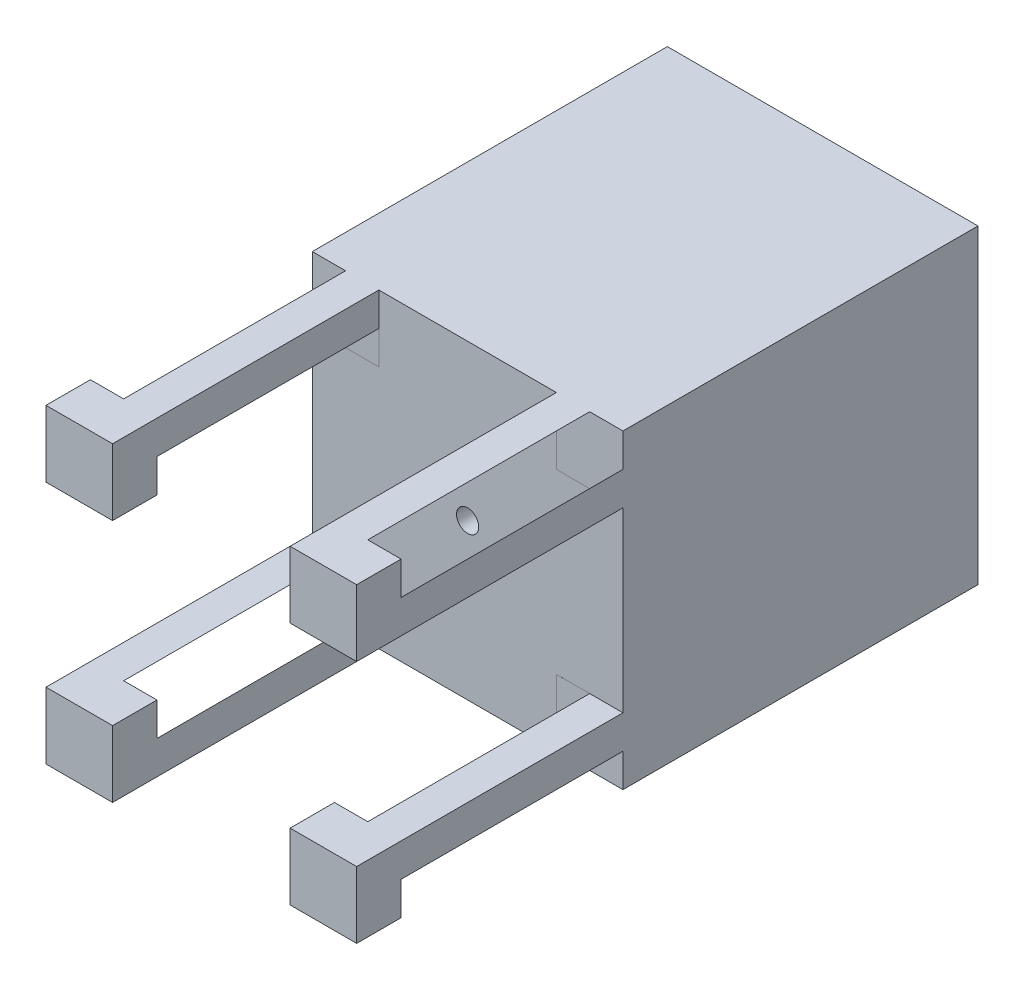
SolidWorks part; units mm, degrees
ref_plane "前视基准面" through (0, 0, 0) normal (0, 0, 1) x (1, 0, 0)
ref_plane "上视基准面" through (0, 0, 0) normal (0, 1, 0) x (1, 0, 0)
ref_plane "右视基准面" through (0, 0, 0) normal (1, 0, 0) x (0, 0, -1)
sketch "草图1" plane through (0, 0, 0) normal (0, 0, 1) x (1, 0, 0)
  line L1 (-27.1705, 16.8017) -> (42.8295, 16.8017)
  line L2 (-27.1705, 16.8017) -> (-27.1705, -53.1983)
  line L3 (-27.1705, -53.1983) -> (42.8295, -53.1983)
  line L4 (42.8295, 16.8017) -> (42.8295, -53.1983)
  line L5 (-12.1547, 0.2553) -> (27.8453, 0.2553)
  line L6 (-12.1547, 0.2553) -> (-12.1547, -39.7447)
  line L7 (-12.1547, -39.7447) -> (27.8453, -39.7447)
  line L8 (27.8453, 0.2553) -> (27.8453, -39.7447)
  line L9 (-12.1547, 0.2553) -> (27.8453, -39.7447) construction
  line L10 (-12.1547, -39.7447) -> (27.8453, 0.2553) construction
  point P4 (7.8453, -19.7447)
  dimension "D1" = 70
  dimension "D2" = 70
  dimension "D3" = 40
  dimension "D4" = 40
extrude "凸台-拉伸1" add sketch "草图1" along normal blind 80
ref_plane "基准面6" through (-12.1547, 0.2553, 80) normal (-1, 0, 0) x (0, 0, 1)
sketch "草图3" plane through (0, 0, 80) normal (0, 0, 1) x (1, 0, 0)
  line L1 (27.8453, 0.2553) -> (-12.1547, 0.2553)
  line L2 (27.8453, 0.2553) -> (27.8453, -39.7447)
  line L3 (27.8453, -39.7447) -> (-12.1547, -39.7447)
  line L4 (-12.1547, 0.2553) -> (-12.1547, -39.7447)
extrude "凸台-拉伸2" add sketch "草图3" against normal blind 15
sketch "草图4" plane through (0, 0, 80) normal (0, 0, 1) x (1, 0, 0)
  circle A0 centre (7.8295, -18.1983) radius 2.5
  dimension "D1" = 5
extrude "切除-拉伸1" cut sketch "草图4" against normal blind 15
sketch "草图5" plane through (0, 0, 65) normal (0, 0, -1) x (-1, 0, 0)
  circle A0 centre (-7.8295, -18.1983) radius 30
  dimension "D1" = 60
extrude "切除-拉伸3" cut sketch "草图5" along normal blind 70
sketch "草图7" plane through (0, 0, 0) normal (0, 0, -1) x (-1, 0, 0)
  line L1 (-17.8295, 10.086) -> (-17.8295, -46.4826)
  line L2 (2.1705, 10.086) -> (2.1705, -46.4826)
  circle A1 centre (-7.8295, -18.1983) radius 30 construction
  circle A2 centre (-7.8295, -18.1983) radius 30 construction
  arc A3 (2.1705, 10.086) -> (2.1705, -46.4826) centre (-7.8295, -18.1983) cw
  arc A4 (-17.8295, 10.086) -> (-17.8295, -46.4826) centre (-7.8295, -18.1983) ccw
extrude "凸台-拉伸4" add sketch "草图7" against normal blind 10
sketch "草图8" plane through (0, 0, 0) normal (0, 0, -1) x (-1, 0, 0)
  line L0 (-17.8295, 11.8017) -> (-17.8295, -48.1983)
  line L1 (-17.8295, -48.1983) -> (2.1048, -48.1983)
  line L2 (-17.8295, 11.8017) -> (2.1048, 11.8017)
  line L3 (2.1048, 11.8017) -> (2.1048, -48.1983)
extrude "切除-拉伸6" cut sketch "草图8" against normal blind 35
sketch "草图9" plane through (0, 0, 80) normal (0, 0, 1) x (1, 0, 0)
  line L1 (-27.1705, -53.1983) -> (-12.1705, -53.1983)
  line L2 (-27.1705, -53.1983) -> (-27.1705, -38.1983)
  line L3 (-27.1705, -38.1983) -> (-12.1705, -38.1983)
  line L4 (-12.1705, -53.1983) -> (-12.1705, -38.1983)
  dimension "D1" = 15
  dimension "D2" = 15
extrude "凸台-拉伸5" add sketch "草图9" along normal blind 0.001 contours L3 L4 L1 L2
sketch "草图10" plane through (0, 0, 80.001) normal (0, 0, 1) x (1, 0, 0)
  line L0 (-27.1705, -38.1983) -> (-19.6705, -38.1983)
  line L1 (-27.1705, -38.1983) -> (-12.1705, -38.1983) construction
  line L2 (-19.6705, -38.1983) -> (-27.1705, -45.6983)
  line L3 (-27.1705, -53.1983) -> (-27.1705, -38.1983) construction
  line L4 (-27.1705, -38.1983) -> (-27.1705, -45.6983)
  line L5 (-19.6705, -53.1983) -> (-12.1705, -53.1983)
  line L6 (-27.1705, -53.1983) -> (-12.1705, -53.1983) construction
  line L7 (-12.1705, -53.1983) -> (-12.1705, -45.6983)
  line L8 (-12.1705, -53.1983) -> (-12.1705, -38.1983) construction
  line L9 (-12.1705, -45.6983) -> (-19.6705, -53.1983)
extrude "凸台-拉伸6" add sketch "草图10" along normal blind 50
sketch "草图11" plane through (0, 0, 130.001) normal (0, 0, 1) x (1, 0, 0)
  line L0 (-27.1705, -38.1983) -> (-27.1705, -53.1983)
  line L1 (-27.1705, -53.1983) -> (-12.1705, -53.1983)
  line L2 (-12.1705, -53.1983) -> (-12.1705, -38.1983)
  line L3 (-12.1705, -38.1983) -> (-27.1705, -38.1983)
extrude "凸台-拉伸7" add sketch "草图11" along normal blind 10
pattern_circular "阵列(圆周)1" count 4 every 90 about axis through (7.8295, -18.1983, 0) along (0, 0, 1) of "凸台-拉伸5", "凸台-拉伸6", "凸台-拉伸7"
